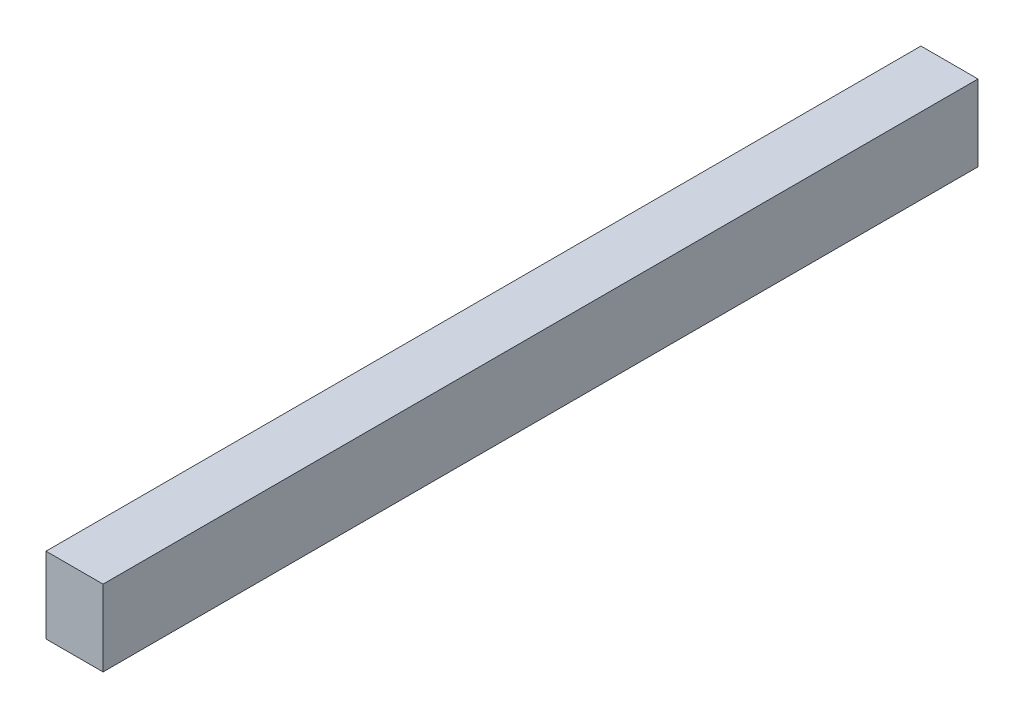
SolidWorks part; units mm, degrees
ref_plane "Front Plane" through (0, 0, 0) normal (0, 0, 1) x (1, 0, 0)
ref_plane "Top Plane" through (0, 0, 0) normal (0, 1, 0) x (1, 0, 0)
ref_plane "Right Plane" through (0, 0, 0) normal (1, 0, 0) x (0, 0, -1)
sketch "Sketch1" plane through (0, 0, 0) normal (0, 0, 1) x (1, 0, 0)
  line L1 (-27.6054, 33.4498) -> (122.3946, 33.4498)
  line L2 (-27.6054, 33.4498) -> (-27.6054, -166.5502)
  line L3 (-27.6054, -166.5502) -> (122.3946, -166.5502)
  line L4 (122.3946, 33.4498) -> (122.3946, -166.5502)
extrude "Boss-Extrude1" add sketch "Sketch1" along normal blind 2300
